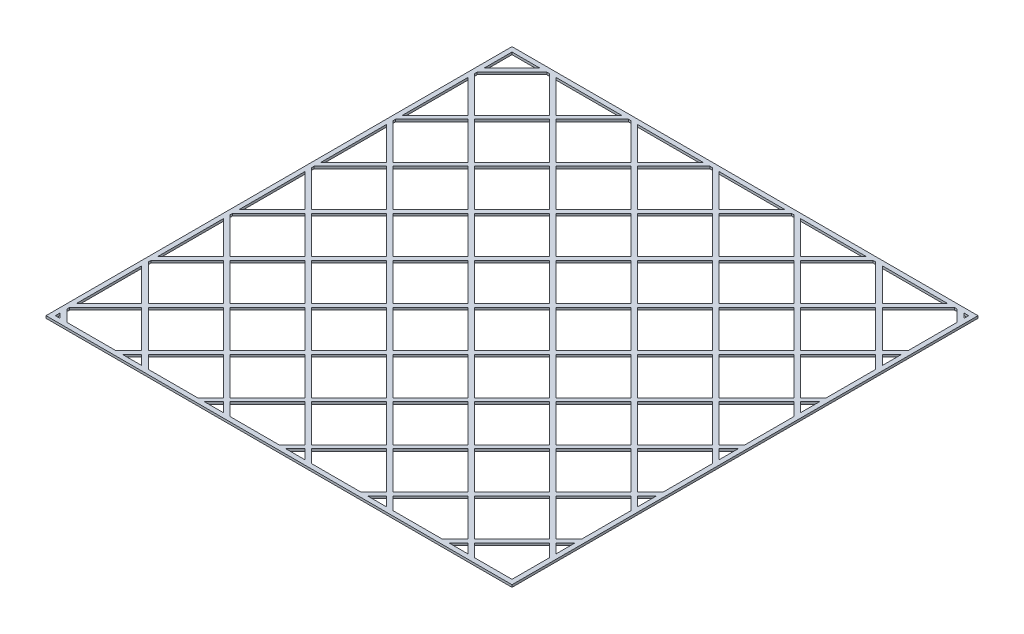
SolidWorks part; units mm, degrees
material "6061 Alloy"
ref_plane "Front Plane" through (0, 0, 0) normal (0, 0, 1) x (1, 0, 0)
ref_plane "Top Plane" through (0, 0, 0) normal (0, 1, 0) x (1, 0, 0)
ref_plane "Right Plane" through (0, 0, 0) normal (1, 0, 0) x (0, 0, -1)
sketch "Sketch1" plane through (0, 0, 0) normal (0, 1, 0) x (1, 0, 0)
  line L1 (-500, -500) -> (500, -500)
  line L2 (-500, -500) -> (-500, 500)
  line L3 (-500, 500) -> (500, 500)
  line L4 (500, -500) -> (500, 500)
  line L5 (-500, -500) -> (500, 500) construction
  line L6 (-500, 500) -> (500, -500) construction
  point P0 (0, 0)
  dimension "D1" = 1000
extrude "Boss-Extrude1" add sketch "Sketch1" along normal mid plane 5
sketch "Sketch2" plane through (0, 2.5, 0) normal (0, 1, 0) x (1, 0, 0)
  line L0 (-412.5, 500) -> (-500, 412.5) construction
  line L1 (-500, 500) -> (-325, 500)
  line L2 (-500, 500) -> (-500, 325)
  line L3 (-500, 325) -> (-325, 325)
  line L4 (-325, 500) -> (-325, 325)
  line L5 (-500, 500) -> (-325, 325) construction
  line L6 (-500, 325) -> (-325, 500) construction
  line L7 (-500, 412.5) -> (-412.5, 325) construction
  line L8 (-412.5, 325) -> (-325, 412.5) construction
  line L9 (-325, 412.5) -> (-412.5, 500) construction
  line L10 (-325, 419.5711) -> (-405.4289, 500)
  line L11 (-419.5711, 500) -> (-500, 419.5711)
  line L12 (-500, 405.4289) -> (-419.5711, 325)
  line L13 (-405.4289, 325) -> (-325, 405.4289)
  line L14 (-332.0711, 412.5) -> (-412.5, 492.9289)
  line L15 (-412.5, 492.9289) -> (-492.9289, 412.5)
  line L16 (-492.9289, 412.5) -> (-412.5, 332.0711)
  line L17 (-412.5, 332.0711) -> (-332.0711, 412.5)
  line L18 (-500, 500) -> (-500, -500) construction
  line L19 (-412.5, 507.0711) -> (-507.0711, 412.5) construction
  line L20 (-507.0711, 412.5) -> (-412.5, 317.9289) construction
  line L21 (-317.9289, 412.5) -> (-412.5, 507.0711) construction
  line L22 (-412.5, 317.9289) -> (-317.9289, 412.5) construction
  line L23 (500, 500) -> (-500, 500) construction
  line L24 (-500, 500) -> (-500, -500)
  line L25 (500, 500) -> (-500, 500)
  point P0 (-412.5, 412.5)
  line M6 (500, 500) -> (-500, 500)
  line M7 (-500, 500) -> (-500, -500)
  dimension "D1" = 175
  dimension "D2" = 5
  dimension "D3" = 5
extrude "Cut-Extrude1" cut sketch "Sketch2" against normal blind 5 contours L11 M6 M7 | L10 L4 M6 | L16 L17 L14 L15 | L13 L3 L4 | L12 L3 M7
pattern_linear "LPattern1" count 6 spacing 175 along (1, 0, 0) count 6 spacing 175 along (0, 0, 1) of "Cut-Extrude1"
sketch "Sketch3" plane through (0, 0, 0) normal (0, 1, 0) x (1, 0, 0)
  line L0 (-490, 490) -> (490, 490)
  line L1 (-500, -500) -> (500, -500)
  line L2 (-500, -500) -> (-500, 500)
  line L3 (-500, 500) -> (500, 500)
  line L4 (500, -500) -> (500, 500)
  line L5 (-500, -500) -> (500, 500) construction
  line L6 (-500, 500) -> (500, -500) construction
  line L7 (490, -490) -> (490, 490)
  line L8 (-490, -490) -> (490, -490)
  line L9 (-490, -490) -> (-490, 490)
  point P0 (0, 0)
  dimension "D1" = 1000
  dimension "D2" = 10
extrude "Boss-Extrude2" add sketch "Sketch3" along normal mid plane 5
equation "\"Dim1Shape\"=175"
equation "\"D1@Sketch2\"=\"Dim1Shape\""
equation "\"D3@LPattern1\"=\"Dim1Shape\""
equation "\"D4@LPattern1\"=\"Dim1Shape\""
equation "\"D1@LPattern1\"=1000/\"Dim1Shape\""
equation "\"D2@LPattern1\"=1000/\"Dim1Shape\""
